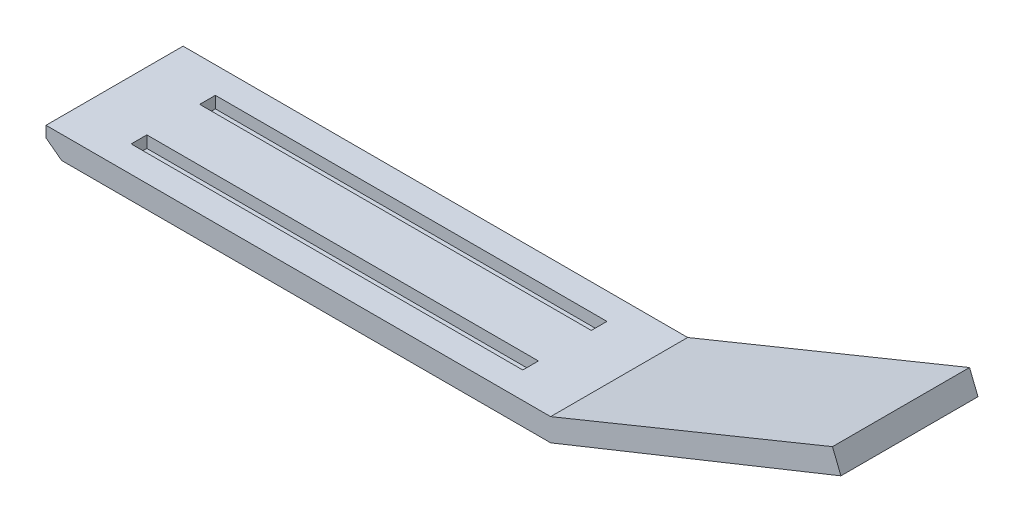
SolidWorks part; units mm, degrees
ref_plane "Alzado" through (0, 0, 0) normal (0, 0, 1) x (1, 0, 0)
ref_plane "Planta" through (0, 0, 0) normal (0, 1, 0) x (1, 0, 0)
ref_plane "Vista lateral" through (0, 0, 0) normal (1, 0, 0) x (0, 0, -1)
sketch "Croquis2" plane through (0, 0, 0) normal (0, 0, 1) x (1, 0, 0)
  line L27 (0, 0) -> (741.337, 297.6249)
  line L28 (0, 0) -> (-1288.663, 0)
  line L30 (0, 58) -> (-1288.663, 58)
  line L31 (-1288.663, 0) -> (-1288.663, 58)
  line L32 (741.337, 297.6249) -> (719.7281, 351.4492)
  line L33 (719.7281, 351.4492) -> (0, 58)
  point P2 (719.319, 352.4682)
  point P5 (0, 0)
  dimension "D1" = 2030
  dimension "D2" = 58
  dimension "D3" = 21.874
  dimension "D4" = 58
extrude "Saliente-Extruir2" add sketch "Croquis2" along normal blind 350
sketch "Croquis3" plane through (0, 0, 350) normal (0, 0, 1) x (1, 0, 0)
  line L0 (-1288.663, 30) -> (-1288.663, 0)
  line L1 (-1288.663, 58) -> (-1288.663, 0) construction
  line L2 (-1288.663, 0) -> (-1248.663, 0)
  line L3 (-1288.663, 0) -> (0, 0) construction
  line L4 (-1248.663, 0) -> (-1288.663, 30)
  dimension "D1" = 30
  dimension "D2" = 40
extrude "Cortar-Extruir1" cut sketch "Croquis3" against normal blind 350
sketch "Croquis4" plane through (0, 58, 0) normal (0, 1, 0) x (1, 0, 0)
  line L1 (-1138.663, -67.5) -> (-138.663, -67.5)
  line L2 (-1138.663, -67.5) -> (-1138.663, -107.5)
  line L3 (-1138.663, -107.5) -> (-138.663, -107.5)
  line L4 (-138.663, -67.5) -> (-138.663, -107.5)
  line L5 (-1138.663, -242.5) -> (-138.663, -242.5)
  line L6 (-1138.663, -242.5) -> (-1138.663, -282.5)
  line L7 (-1138.663, -282.5) -> (-138.663, -282.5)
  line L8 (-138.663, -242.5) -> (-138.663, -282.5)
  line L9 (-1288.663, -350) -> (-1288.663, 0) construction
  line L11 (0, -350) -> (-1288.663, -350) construction
  line L12 (0, 0) -> (-1288.663, 0) construction
  dimension "D1" = 40
  dimension "D2" = 40
  dimension "D3" = 150
  dimension "D4" = 150
  dimension "D5" = 67.5
  dimension "D6" = 67.5
  dimension "D7" = 1000
  dimension "D8" = 1000
extrude "Cortar-Extruir2" cut sketch "Croquis4" against normal blind 30
